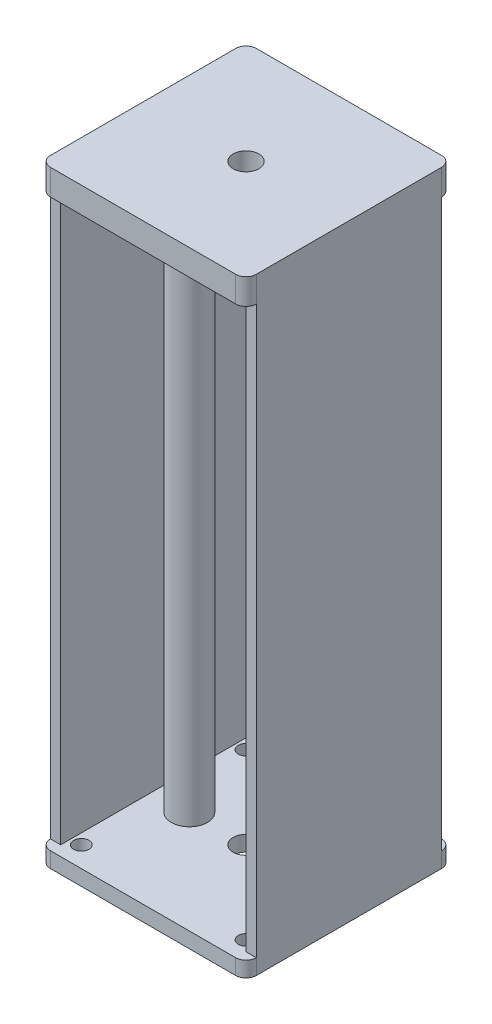
SolidWorks part; units mm, degrees
material "1023 Carbon Steel Sheet (SS)"
ref_plane "Front Plane" through (0, 0, 0) normal (0, 0, 1) x (1, 0, 0)
ref_plane "Top Plane" through (0, 0, 0) normal (0, 1, 0) x (1, 0, 0)
ref_plane "Right Plane" through (0, 0, 0) normal (1, 0, 0) x (0, 0, -1)
sketch "Sketch1" plane through (0, 0, 0) normal (0, 1, 0) x (1, 0, 0)
  line L0 (0, 0) -> (0, -40)
  line L1 (0, -40) -> (40, -40)
  line L2 (40, -40) -> (40, 0)
  line L3 (40, 0) -> (0, 0)
  dimension "D1" = 40
  dimension "D2" = 40
extrude "Boss-Extrude1" add sketch "Sketch1" along normal blind 5
fillet "Fillet1" radius 2 4 edges at (0, 2.5, 40) (0, 2.5, 0) (40, 2.5, 0) (40, 2.5, 40)
sketch "Sketch2" plane through (0, 0, 0) normal (0, -1, 0) x (1, 0, 0)
  line L0 (0, 38) -> (0, 2)
  line L1 (0, 2) -> (2, 2)
  line L2 (2, 2) -> (2, 38)
  line L3 (2, 38) -> (0, 38)
  line L4 (40, 38) -> (38, 38)
  line L5 (40, 38) -> (40, 2) construction
  line L6 (38, 38) -> (38, 2)
  line L7 (38, 2) -> (40, 2)
  line L8 (40, 2) -> (40, 38)
  arc A0 (40, 38) -> (38, 40) centre (38, 38) ccw construction
  dimension "D1" = 2
extrude "Boss-Extrude2" add sketch "Sketch2" along normal blind 110
sketch "Sketch3" plane through (0, -110, 0) normal (0, -1, 0) x (1, 0, 0)
  line L1 (0, 0) -> (40, 0)
  line L2 (0, 0) -> (0, 40)
  line L3 (0, 40) -> (40, 40)
  line L4 (40, 0) -> (40, 40)
extrude "Boss-Extrude3" add sketch "Sketch3" along normal blind 3
fillet "Fillet2" radius 2 4 edges at (0, -111.5, 0) (40, -111.5, 0) (40, -111.5, 40) (0, -111.5, 40)
sketch "Sketch4" plane through (0, -113, 0) normal (0, -1, 0) x (1, 0, 0)
  line L1 (0, 38) -> (0, 2) construction
  circle A0 centre (4, 4) radius 1.5
  circle A1 centre (36, 4) radius 1.5
  circle A2 centre (4, 36) radius 1.5
  circle A3 centre (36, 36) radius 1.5
  dimension "D6" = 3
  dimension "D7" = 3
  dimension "D8" = 3
  dimension "D9" = 3
  dimension "D1" = 32
  dimension "D2" = 32
  dimension "D3" = 32
  dimension "D4" = 32
  dimension "D5" = 0
  dimension "D11" = 4
  dimension "D12" = 4
extrude "Cut-Extrude1" cut sketch "Sketch4" against normal blind 10
sketch "Sketch5" plane through (0, 0, 0) normal (0, 1, 0) x (1, 0, 0)
  circle A0 centre (20, -20) radius 2.5
  dimension "D1" = 5
extrude "Cut-Extrude2" cut sketch "Sketch5" along normal through all
sketch "Sketch6" plane through (0, -113, 0) normal (0, -1, 0) x (1, 0, 0)
  circle A0 centre (20, 20) radius 2.5
  dimension "D1" = 5
extrude "Cut-Extrude4" cut sketch "Sketch6" against normal through all
sketch "Sketch8" plane through (0, -110, 0) normal (0, 1, 0) x (1, 0, 0)
  line L0 (0, 0) -> (0, -40) construction
  line L1 (40, -40) -> (40, 0) construction
  line L2 (0, -40) -> (40, -40) construction
  circle A0 centre (9, -20) radius 3.5
  circle A1 centre (31, -20) radius 3.5
  dimension "D1" = 7
  dimension "D2" = 7
  dimension "D3" = 9
  dimension "D4" = 9
  dimension "D5" = 22
  dimension "D6" = 20
extrude "Boss-Extrude4" add sketch "Sketch8" along normal blind 114
